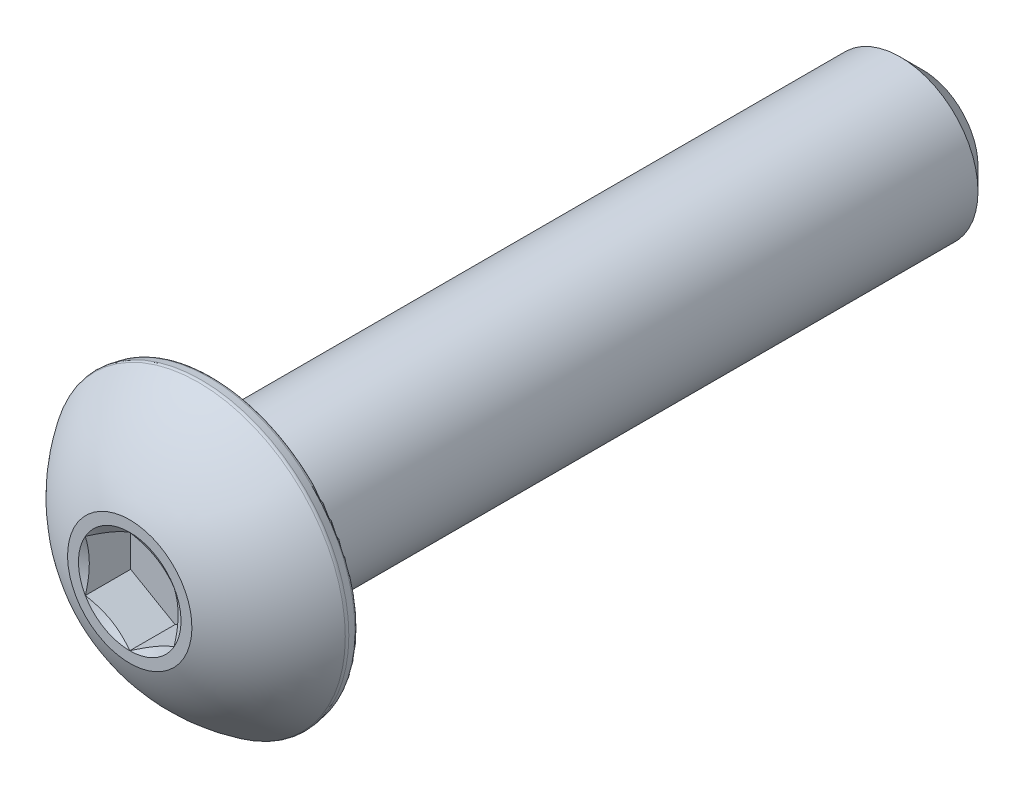
SolidWorks part; units mm, degrees
ref_plane "Front Plane" through (0, 0, 0) normal (0, 0, 1) x (1, 0, 0)
ref_plane "Top Plane" through (0, 0, 0) normal (0, 1, 0) x (1, 0, 0)
ref_plane "Right Plane" through (0, 0, 0) normal (1, 0, 0) x (0, 0, -1)
sketch "Sketch1" plane through (0, 0, 0) normal (1, 0, 0) x (0, 0, -1)
  line L0 (-10.6299, 0) -> (10.6299, 0) construction
  line L1 (-10.6299, 0) -> (-10.6299, 3.9624)
  line L2 (-10.6299, 3.9624) -> (-8.4201, 3.9624)
  line L3 (-8.4201, 3.9624) -> (-8.4201, 2.0828)
  line L4 (-8.4201, 2.0828) -> (10.6299, 2.0828)
  line L5 (10.6299, 2.0828) -> (10.6299, 0)
  point P2 (0, 0)
  point P4 (9.8361, 0)
  point P9 (9.4393, 2.0828)
  point P10 (9.4393, -2.0828)
  point P11 (10.6299, -2.0828)
  point P15 (-9.4145, 0)
  dimension "Head Height" = 2.2098
  dimension "Head Diameter" = 7.9248
  dimension "Length" = 19.05
  dimension "Screw Size Decimal Equivalent" = 4.1656
  dimension "Thread Pitch" = 0.7937
  dimension "D1" = 1.1906
  dimension "D2" = 1.2154
sketch "Sketch2" plane through (0, 0, 0) normal (0, 0, 1) x (1, 0, 0)
  line L0 (0, 2.0828) -> (0, 0) construction
  line L1 (0, 1.3748) -> (-1.1906, 0.6874)
  line L2 (-1.1906, 0.6874) -> (-1.1906, -0.6874)
  line L3 (-1.1906, -0.6874) -> (0, -1.3748)
  line L4 (0, -1.3748) -> (1.1906, -0.6874)
  line L5 (1.1906, -0.6874) -> (1.1906, 0.6874)
  line L6 (1.1906, 0.6874) -> (0, 1.3748)
  circle A0 centre (0, 0) radius 1.1906 construction
  circle A1 centre (0, 0) radius 1.6669
  point P10 (0, 1.6669)
  dimension "D1" = 3.3337
  dimension "Drive Size" = 2.3813
sketch "Sketch3" plane through (0, 0, 0) normal (1, 0, 0) x (0, 0, -1)
  line L0 (-10.6299, 0) -> (-10.6299, 1.6669)
  line L1 (-10.6299, 0) -> (-10.6299, 3.9624) construction
  line L2 (-10.6299, 3.9624) -> (-8.4201, 3.9624) construction
  line L3 (-8.7516, 3.9624) -> (-8.4201, 3.904)
  line L4 (-8.4201, 3.9624) -> (-8.4201, 2.0828) construction
  line L5 (-8.4201, 3.904) -> (-8.4201, 2.0828)
  line L6 (-10.6299, 0) -> (10.6299, 0) construction
  line L7 (-10.6299, 0) -> (10.6299, 0)
  line L8 (10.6299, 0) -> (10.6299, 1.4875)
  line L9 (10.6299, 2.0828) -> (10.6299, 0) construction
  line L10 (10.6299, 1.4875) -> (10.0346, 2.0828)
  line L11 (-8.4201, 2.0828) -> (10.6299, 2.0828) construction
  line L12 (10.0346, 2.0828) -> (-8.4201, 2.0828)
  arc A0 (-10.6299, 1.6669) -> (-8.7516, 3.9624) centre (-6.2509, 0) cw
  dimension "D1" = 0.3315
  dimension "D2" = 10
  dimension "D3" = 45
  dimension "D4" = 0.5953
revolve "Revolve1" add sketch "Sketch3" angle 360 about L7
sketch "Sketch4" plane through (0, 0, 10.6299) normal (0, 0, 1) x (1, 0, 0)
  line L0 (-1.1906, -0.6874) -> (0, -1.3748) construction
  line L1 (-1.1906, 0.6874) -> (-1.1906, -0.6874) construction
  line L2 (0, 1.3748) -> (-1.1906, 0.6874) construction
  line L3 (1.1906, 0.6874) -> (0, 1.3748) construction
  line L4 (1.1906, -0.6874) -> (1.1906, 0.6874) construction
  line L5 (0, -1.3748) -> (1.1906, -0.6874) construction
  line L6 (-1.1906, -0.6874) -> (0, -1.3748)
  line L7 (-1.1906, 0.6874) -> (-1.1906, -0.6874)
  line L8 (0, 1.3748) -> (-1.1906, 0.6874)
  line L9 (1.1906, 0.6874) -> (0, 1.3748)
  line L10 (1.1906, -0.6874) -> (1.1906, 0.6874)
  line L11 (0, -1.3748) -> (1.1906, -0.6874)
extrude "Cut-Extrude1" cut sketch "Sketch4" against normal up to vertex (1.2154 mm away) up to point (0, 0, 9.4145)
sketch "Sketch5" plane through (0, 0, 10.6299) normal (0, 0, 1) x (1, 0, 0)
  circle A0 centre (0, 0) radius 1.3748
extrude "Cut-Extrude2" cut sketch "Sketch5" against normal up to vertex (1.2154 mm away) draft 60 up to point (0, 0, 9.4145)
fillet "Fillet1" radius 0.1105 2 edges at (3.9624, 0, 8.7516) (3.904, 0, 8.4201)
equation "\"D1@Sketch1\"=\"Thread Pitch@Sketch1\"*1.5"
equation "\"D2@Sketch1\"=0.55*\"Head Height@Sketch1\""
equation "\"D1@Sketch2\"=\"Drive Size@Sketch2\"*1.4"
equation "\"D1@Sketch3\"=0.15*\"Head Height@Sketch1\""
equation "\"D4@Sketch3\"=0.75*\"Thread Pitch@Sketch1\""
equation "\"D1@Fillet1\"=.05*\"Head Height@Sketch1\""
